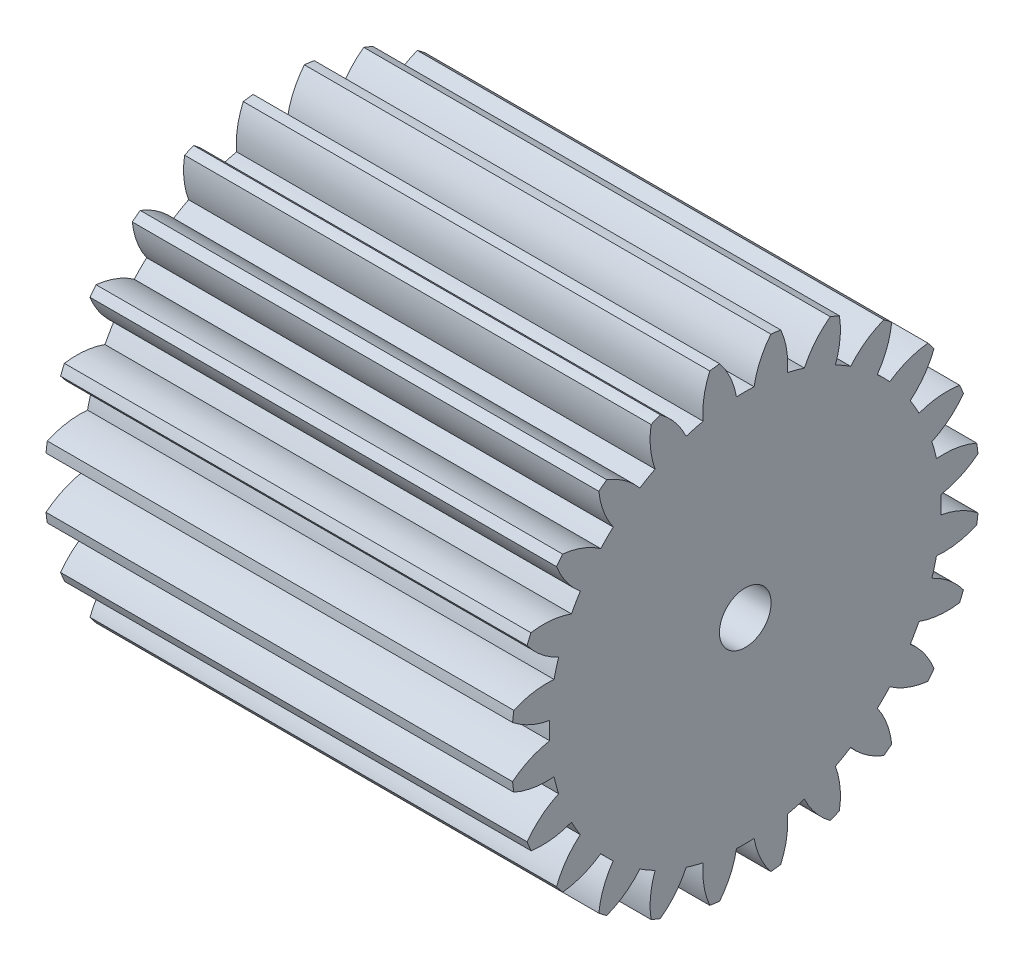
SolidWorks part; units mm, degrees
ref_plane "Front Plane" through (0, 0, 0) normal (0, 0, 1) x (1, 0, 0)
ref_plane "Top Plane" through (0, 0, 0) normal (0, 1, 0) x (1, 0, 0)
ref_plane "Right Plane" through (0, 0, 0) normal (1, 0, 0) x (0, 0, -1)
ref_plane "Plane1" through (-24.0362, 0, 0) normal (1, 0, 0) x (0, 0, -1)
sketch "Sketch1" plane through (-24.0362, 0, 0) normal (1, 0, 0) x (0, 0, -1)
  circle A0 centre (-6.492, 13.4059) radius 1.55
  arc A1 (-20.4597, 14.9437) -> (-18.2301, 13.9343) centre (-17.3829, 18.7728) ccw
  arc A2 (-18.2301, 13.9343) -> (-18.2301, 12.8774) centre (-6.492, 13.4059) ccw
  arc A3 (-18.2301, 12.8774) -> (-20.4597, 11.8681) centre (-17.3829, 8.0389) ccw
  arc A4 (-20.4597, 11.8681) -> (-20.3817, 11.2762) centre (-6.492, 13.4059) ccw
  arc A5 (-20.3817, 11.2762) -> (-17.9669, 10.8783) centre (-18.4009, 15.7712) ccw
  arc A6 (-17.9669, 10.8783) -> (-17.6933, 9.8574) centre (-6.492, 13.4059) ccw
  arc A7 (-17.6933, 9.8574) -> (-19.5857, 8.3054) centre (-15.6228, 5.403) ccw
  arc A8 (-19.5857, 8.3054) -> (-19.3377, 7.7095) centre (-6.492, 13.4059) ccw
  arc A9 (-19.3377, 7.7095) -> (-16.9217, 7.9945) centre (-18.6873, 12.5783) ccw
  arc A10 (-16.9217, 7.9945) -> (-16.3932, 7.0792) centre (-6.492, 13.4059) ccw
  arc A11 (-16.3932, 7.0792) -> (-17.8194, 5.0903) centre (-13.2403, 3.3125) ccw
  arc A12 (-17.8194, 5.0903) -> (-17.456, 4.6166) centre (-6.492, 13.4059) ccw
  arc A13 (-17.456, 4.6166) -> (-15.1658, 5.4795) centre (-17.9881, 9.4998) ccw
  arc A14 (-15.1658, 5.4795) -> (-14.4184, 4.7321) centre (-6.492, 13.4059) ccw
  arc A15 (-14.4184, 4.7321) -> (-15.2812, 2.4418) centre (-10.398, 1.9098) ccw
  arc A16 (-15.2812, 2.4418) -> (-14.8076, 2.0784) centre (-6.492, 13.4059) ccw
  arc A17 (-14.8076, 2.0784) -> (-12.8187, 3.5046) centre (-16.5854, 6.6575) ccw
  arc A18 (-12.8187, 3.5046) -> (-11.9034, 2.9761) centre (-6.492, 13.4059) ccw
  arc A19 (-11.9034, 2.9761) -> (-12.144, 0.5406) centre (-7.2895, 1.2906) ccw
  arc A20 (-12.144, 0.5406) -> (-11.5925, 0.3121) centre (-6.492, 13.4059) ccw
  arc A21 (-11.5925, 0.3121) -> (-10.0405, 2.2045) centre (-14.4948, 4.2751) ccw
  arc A22 (-10.0405, 2.2045) -> (-9.0196, 1.931) centre (-6.492, 13.4059) ccw
  arc A23 (-9.0196, 1.931) -> (-8.6217, -0.4839) centre (-4.1267, 1.497) ccw
  arc A24 (-8.6217, -0.4839) -> (-8.0298, -0.5618) centre (-6.492, 13.4059) ccw
  arc A25 (-8.0298, -0.5618) -> (-7.0205, 1.6678) centre (-11.8589, 2.5149) ccw
  arc A26 (-7.0205, 1.6678) -> (-5.9635, 1.6678) centre (-6.492, 13.4059) ccw
  arc A27 (-5.9635, 1.6678) -> (-4.9542, -0.5618) centre (-1.125, 2.5149) ccw
  arc A28 (-4.9542, -0.5618) -> (-4.3623, -0.4839) centre (-6.492, 13.4059) ccw
  arc A29 (-4.3623, -0.4839) -> (-3.9644, 1.931) centre (-8.8573, 1.497) ccw
  arc A30 (-3.9644, 1.931) -> (-2.9435, 2.2045) centre (-6.492, 13.4059) ccw
  arc A31 (-2.9435, 2.2045) -> (-1.3915, 0.3121) centre (1.5109, 4.2751) ccw
  arc A32 (-1.3915, 0.3121) -> (-0.8399, 0.5406) centre (-6.492, 13.4059) ccw
  arc A33 (-0.8399, 0.5406) -> (-1.0806, 2.9761) centre (-5.6944, 1.2906) ccw
  arc A34 (-1.0806, 2.9761) -> (-0.1653, 3.5046) centre (-6.492, 13.4059) ccw
  arc A35 (-0.1653, 3.5046) -> (1.8236, 2.0784) centre (3.6014, 6.6575) ccw
  arc A36 (1.8236, 2.0784) -> (2.2973, 2.4418) centre (-6.492, 13.4059) ccw
  arc A37 (2.2973, 2.4418) -> (1.4344, 4.7321) centre (-2.5859, 1.9098) ccw
  arc A38 (1.4344, 4.7321) -> (2.1818, 5.4795) centre (-6.492, 13.4059) ccw
  arc A39 (2.1818, 5.4795) -> (4.4721, 4.6166) centre (5.0041, 9.4998) ccw
  arc A40 (4.4721, 4.6166) -> (4.8355, 5.0903) centre (-6.492, 13.4059) ccw
  arc A41 (4.8355, 5.0903) -> (3.4093, 7.0792) centre (0.2564, 3.3125) ccw
  arc A42 (3.4093, 7.0792) -> (3.9378, 7.9945) centre (-6.492, 13.4059) ccw
  arc A43 (3.9378, 7.9945) -> (6.3733, 7.7538) centre (5.6233, 12.6083) ccw
  arc A44 (6.3733, 7.7538) -> (6.6017, 8.3054) centre (-6.492, 13.4059) ccw
  arc A45 (6.6017, 8.3054) -> (4.7094, 9.8574) centre (2.6388, 5.403) ccw
  arc A46 (4.7094, 9.8574) -> (4.9829, 10.8783) centre (-6.492, 13.4059) ccw
  arc A47 (4.9829, 10.8783) -> (7.3978, 11.2762) centre (5.4169, 15.7712) ccw
  arc A48 (7.3978, 11.2762) -> (7.4757, 11.8681) centre (-6.492, 13.4059) ccw
  arc A49 (7.4757, 11.8681) -> (5.2461, 12.8774) centre (4.399, 8.0389) ccw
  arc A50 (5.2461, 12.8774) -> (5.2461, 13.9343) centre (-6.492, 13.4059) ccw
  arc A51 (5.2461, 13.9343) -> (7.4757, 14.9437) centre (4.399, 18.7728) ccw
  arc A52 (7.4757, 14.9437) -> (7.3978, 15.5356) centre (-6.492, 13.4059) ccw
  arc A53 (7.3978, 15.5356) -> (4.9829, 15.9335) centre (5.4169, 11.0406) ccw
  arc A54 (4.9829, 15.9335) -> (4.7094, 16.9544) centre (-6.492, 13.4059) ccw
  arc A55 (4.7094, 16.9544) -> (6.6017, 18.5064) centre (2.6388, 21.4087) ccw
  arc A56 (6.6017, 18.5064) -> (6.3733, 19.0579) centre (-6.492, 13.4059) ccw
  arc A57 (6.3733, 19.0579) -> (3.9378, 18.8173) centre (5.6233, 14.2034) ccw
  arc A58 (3.9378, 18.8173) -> (3.4093, 19.7326) centre (-6.492, 13.4059) ccw
  arc A59 (3.4093, 19.7326) -> (4.8355, 21.7215) centre (0.2564, 23.4993) ccw
  arc A60 (4.8355, 21.7215) -> (4.4721, 22.1951) centre (-6.492, 13.4059) ccw
  arc A61 (4.4721, 22.1951) -> (2.1818, 21.3323) centre (5.0041, 17.3119) ccw
  arc A62 (2.1818, 21.3323) -> (1.4344, 22.0797) centre (-6.492, 13.4059) ccw
  arc A63 (1.4344, 22.0797) -> (2.2973, 24.3699) centre (-2.5859, 24.9019) ccw
  arc A64 (2.2973, 24.3699) -> (1.8236, 24.7333) centre (-6.492, 13.4059) ccw
  arc A65 (1.8236, 24.7333) -> (-0.1653, 23.3071) centre (3.6014, 20.1542) ccw
  arc A66 (-0.1653, 23.3071) -> (-1.0806, 23.8356) centre (-6.492, 13.4059) ccw
  arc A67 (-1.0806, 23.8356) -> (-0.8399, 26.2711) centre (-5.6944, 25.5212) ccw
  arc A68 (-0.8399, 26.2711) -> (-1.3915, 26.4996) centre (-6.492, 13.4059) ccw
  arc A69 (-1.3915, 26.4996) -> (-2.9435, 24.6072) centre (1.5109, 22.5367) ccw
  arc A70 (-2.9435, 24.6072) -> (-3.9644, 24.8808) centre (-6.492, 13.4059) ccw
  arc A71 (-3.9644, 24.8808) -> (-4.3623, 27.2956) centre (-8.8573, 25.3148) ccw
  arc A72 (-4.3623, 27.2956) -> (-4.9542, 27.3736) centre (-6.492, 13.4059) ccw
  arc A73 (-4.9542, 27.3736) -> (-5.9635, 25.144) centre (-1.125, 24.2968) ccw
  arc A74 (-5.9635, 25.144) -> (-7.0205, 25.144) centre (-6.492, 13.4059) ccw
  arc A75 (-7.0205, 25.144) -> (-8.0298, 27.3736) centre (-11.8589, 24.2968) ccw
  arc A76 (-8.0298, 27.3736) -> (-8.6217, 27.2956) centre (-6.492, 13.4059) ccw
  arc A77 (-8.6217, 27.2956) -> (-9.0196, 24.8808) centre (-4.1267, 25.3148) ccw
  arc A78 (-9.0196, 24.8808) -> (-10.0405, 24.6072) centre (-6.492, 13.4059) ccw
  arc A79 (-10.0405, 24.6072) -> (-11.5925, 26.4996) centre (-14.4948, 22.5367) ccw
  arc A80 (-11.5925, 26.4996) -> (-12.144, 26.2711) centre (-6.492, 13.4059) ccw
  arc A81 (-12.144, 26.2711) -> (-11.9034, 23.8356) centre (-7.2895, 25.5212) ccw
  arc A82 (-11.9034, 23.8356) -> (-12.8187, 23.3071) centre (-6.492, 13.4059) ccw
  arc A83 (-12.8187, 23.3071) -> (-14.8076, 24.7333) centre (-16.5854, 20.1542) ccw
  arc A84 (-14.8076, 24.7333) -> (-15.2812, 24.3699) centre (-6.492, 13.4059) ccw
  arc A85 (-15.2812, 24.3699) -> (-14.4184, 22.0797) centre (-10.398, 24.9019) ccw
  arc A86 (-14.4184, 22.0797) -> (-15.1658, 21.3323) centre (-6.492, 13.4059) ccw
  arc A87 (-15.1658, 21.3323) -> (-17.456, 22.1951) centre (-17.9881, 17.3119) ccw
  arc A88 (-17.456, 22.1951) -> (-17.8194, 21.7215) centre (-6.492, 13.4059) ccw
  arc A89 (-17.8194, 21.7215) -> (-16.3932, 19.7326) centre (-13.2403, 23.4993) ccw
  arc A90 (-16.3932, 19.7326) -> (-16.9217, 18.8173) centre (-6.492, 13.4059) ccw
  arc A91 (-16.9217, 18.8173) -> (-19.3573, 19.0579) centre (-18.6073, 14.2034) ccw
  arc A92 (-19.3573, 19.0579) -> (-19.5857, 18.5064) centre (-6.492, 13.4059) ccw
  arc A93 (-19.5857, 18.5064) -> (-17.6933, 16.9544) centre (-15.6228, 21.4087) ccw
  arc A94 (-17.6933, 16.9544) -> (-17.9669, 15.9335) centre (-6.492, 13.4059) ccw
  arc A95 (-17.9669, 15.9335) -> (-20.3817, 15.5356) centre (-18.4009, 11.0406) ccw
  arc A96 (-20.3817, 15.5356) -> (-20.4597, 14.9437) centre (-6.492, 13.4059) ccw
  dimension "D1" = 11.75
  dimension "D2" = 3.1
extrude "Boss-Extrude1" add sketch "Sketch1" against normal blind 28
